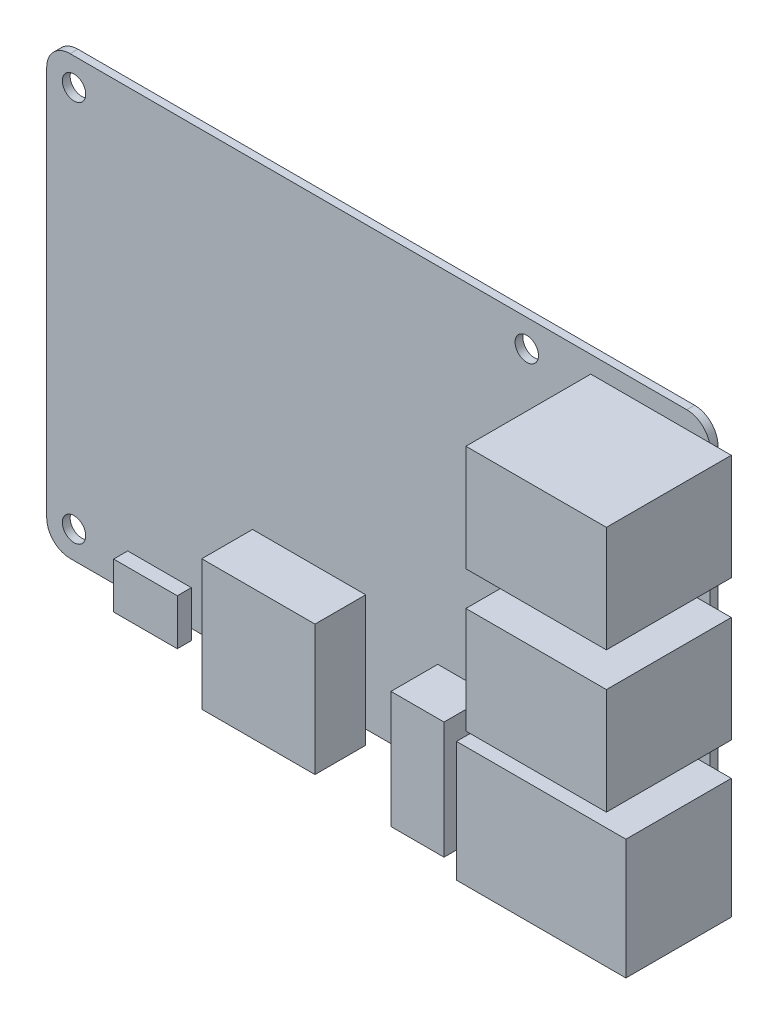
SolidWorks part; units mm, degrees
ref_plane "Plan de face" through (0, 0, 0) normal (0, 0, 1) x (1, 0, 0)
ref_plane "Plan de dessus" through (0, 0, 0) normal (0, 1, 0) x (1, 0, 0)
ref_plane "Plan de droite" through (0, 0, 0) normal (1, 0, 0) x (0, 0, -1)
sketch "Esquisse1" plane through (0, 0, 0) normal (0, 0, 1) x (1, 0, 0)
  line L1 (-44.1081, 24.0068) -> (40.8919, 24.0068)
  line L2 (-44.1081, 24.0068) -> (-44.1081, -31.9932)
  line L3 (-44.1081, -31.9932) -> (40.8919, -31.9932)
  line L4 (40.8919, 24.0068) -> (40.8919, -31.9932)
  dimension "D1" = 85
  dimension "D2" = 56
extrude "Boss.-Extru.1" add sketch "Esquisse1" along normal blind 1 contours L1 L4 L3 L2
fillet "Congé3" radius 3 1 edges at (40.8919, 24.0068, 0.5)
fillet "Congé4" radius 3 1 edges at (-44.1081, 24.0068, 0.5)
fillet "Congé5" radius 3 1 edges at (-44.1081, -31.9932, 0.5)
fillet "Congé6" radius 3 1 edges at (40.8919, -31.9932, 0.5)
sketch "Esquisse2" plane through (0, 0, 1) normal (0, 0, 1) x (1, 0, 0)
  line L0 (-41.1081, 24.0068) -> (37.8919, 24.0068) construction
  line L2 (-44.1081, 21.0068) -> (-44.1081, -28.9932) construction
  circle A0 centre (-40.6081, 20.5068) radius 1.5
  circle A1 centre (-40.6081, -28.4932) radius 1.5
  circle A2 centre (17.3919, -28.4932) radius 1.5
  circle A3 centre (17.3919, 20.5068) radius 1.5
  dimension "D1" = 3.5
  dimension "D2" = 3.5
  dimension "D3" = 2
  dimension "D4" = 2
extrude "Enlèv. mat.-Extru.1" cut sketch "Esquisse2" against normal through all
sketch "Esquisse3" plane through (0, 0, 1) normal (0, 0, 1) x (1, 0, 0)
  line L0 (40.8919, 21.0068) -> (40.8919, -28.9932) construction
  line L1 (40.8919, 21.8068) -> (25.5919, 21.8068)
  line L2 (40.8919, 21.8068) -> (40.8919, 8.2068)
  line L3 (40.8919, 8.2068) -> (25.5919, 8.2068)
  line L4 (25.5919, 21.8068) -> (25.5919, 8.2068)
  line L5 (25.5919, 21.8068) -> (40.8919, 8.2068) construction
  line L6 (40.8919, 21.8068) -> (25.5919, 8.2068) construction
  line L7 (-41.1081, -31.9932) -> (37.8919, -31.9932) construction
  point P6 (33.2419, 15.0068)
  dimension "D1" = 13.6
  dimension "D2" = 15.3
  dimension "D3" = 47
extrude "Boss.-Extru.3" add sketch "Esquisse3" along normal blind 16 contours L1 L4 L3 L2
sketch "Esquisse5" plane through (40.8919, 0, 0) normal (1, 0, 0) x (0, 0, -1)
  line L1 (-17, 21.8068) -> (-1, 21.8068)
  line L2 (-17, 21.8068) -> (-17, 8.2068)
  line L3 (-17, 8.2068) -> (-1, 8.2068)
  line L4 (-1, 21.8068) -> (-1, 8.2068)
extrude "Boss.-Extru.4" add sketch "Esquisse5" along normal blind 2.7
pattern_linear "Répétition linéaire1" count 2 spacing 18 along (0, -1, 0) of "Boss.-Extru.3"
pattern_linear "Répétition linéaire2" count 2 spacing 18 along (0, -1, 0) of "Boss.-Extru.4"
sketch "Esquisse7" plane through (0, 0, 1) normal (0, 0, 1) x (1, 0, 0)
  line L0 (40.8919, -9.7932) -> (40.8919, -28.9932) construction
  line L1 (21.8919, -14.0432) -> (43.5919, -14.0432)
  line L2 (21.8919, -14.0432) -> (21.8919, -29.4432)
  line L3 (21.8919, -29.4432) -> (43.5919, -29.4432)
  line L4 (43.5919, -14.0432) -> (43.5919, -29.4432)
  line L5 (21.8919, -14.0432) -> (43.5919, -29.4432) construction
  line L6 (43.5919, -14.0432) -> (21.8919, -29.4432) construction
  line L7 (-41.1081, -31.9932) -> (37.8919, -31.9932) construction
  point P6 (32.7419, -21.7432)
  dimension "D1" = 21.7
  dimension "D2" = 2.7
  dimension "D3" = 15.4
  dimension "D4" = 10.25
extrude "Boss.-Extru.5" add sketch "Esquisse7" along normal blind 13.5 contours L4 L3 L2 L1
sketch "Esquisse8" plane through (0, 0, 1) normal (0, 0, 1) x (1, 0, 0)
  line L0 (12.7919, -20.1932) -> (5.9919, -35.1932) construction
  line L1 (5.9919, -20.1932) -> (12.7919, -20.1932)
  line L2 (5.9919, -20.1932) -> (5.9919, -35.1932)
  line L3 (5.9919, -35.1932) -> (12.7919, -35.1932)
  line L4 (12.7919, -20.1932) -> (12.7919, -35.1932)
  line L5 (-44.1081, 21.0068) -> (-44.1081, -28.9932) construction
  line L6 (-41.1081, -31.9932) -> (37.8919, -31.9932) construction
  point P4 (9.3919, -27.6932)
  dimension "D1" = 53.5
  dimension "D2" = 15
  dimension "D3" = 6.8
  dimension "D4" = 3.2
extrude "Boss.-Extru.6" add sketch "Esquisse8" along normal blind 6
sketch "Esquisse9" plane through (0, 0, 1) normal (0, 0, 1) x (1, 0, 0)
  line L0 (-41.1081, -31.9932) -> (5.9919, -31.9932) construction
  line L1 (-17.7417, -17.0932) -> (-3.2417, -17.0932)
  line L2 (-17.7417, -17.0932) -> (-17.7417, -33.7932)
  line L3 (-17.7417, -33.7932) -> (-3.2417, -33.7932)
  line L4 (-3.2417, -17.0932) -> (-3.2417, -33.7932)
  dimension "D1" = 14.5
  dimension "D2" = 16.7
  dimension "D3" = 1.8
extrude "Boss.-Extru.7" add sketch "Esquisse9" along normal blind 6.5
sketch "Esquisse10" plane through (0, 0, 1) normal (0, 0, 1) x (1, 0, 0)
  line L0 (-41.1081, -31.9932) -> (-17.7417, -31.9932) construction
  line L1 (-33.7331, -27.4732) -> (-25.5831, -27.4732)
  line L2 (-33.7331, -27.4732) -> (-33.7331, -33.3532)
  line L3 (-33.7331, -33.3532) -> (-25.5831, -33.3532)
  line L4 (-25.5831, -27.4732) -> (-25.5831, -33.3532)
  dimension "D1" = 8.15
  dimension "D2" = 5.88
  dimension "D3" = 1.36
extrude "Boss.-Extru.8" add sketch "Esquisse10" along normal blind 1.8
